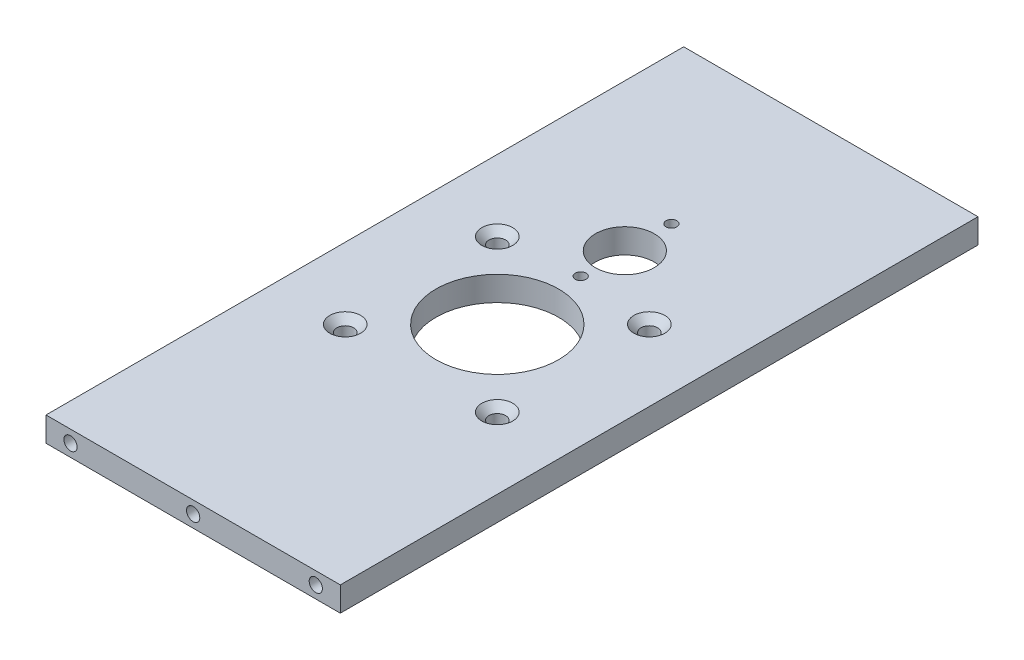
SolidWorks part; units mm, degrees
ref_plane "前基準面" through (0, 0, 0) normal (0, 0, 1) x (1, 0, 0)
ref_plane "上基準面" through (0, 0, 0) normal (0, 1, 0) x (1, 0, 0)
ref_plane "右基準面" through (0, 0, 0) normal (1, 0, 0) x (0, 0, -1)
sketch "草圖1" plane through (0, 0, 0) normal (0, 1, 0) x (1, 0, 0)
  line L1 (-30, -65) -> (30, -65)
  line L2 (-30, -65) -> (-30, 65)
  line L3 (-30, 65) -> (30, 65)
  line L4 (30, -65) -> (30, 65)
  line L5 (-30, -65) -> (30, 65) construction
  line L6 (-30, 65) -> (30, -65) construction
  point P0 (0, 0)
  dimension "D1" = 60
  dimension "D2" = 130
extrude "填料-伸長1" add sketch "草圖1" along normal blind 5
hole_wizard "M3 錐坑平頭螺釘的錐孔1" positions "草圖4" profile "草圖5" countersink size "M3" standard "ISO"
sketch "草圖4" plane through (0, 5, 0) normal (0, 1, 0) x (1, 0, 0)
  line L0 (-15.5, 12.5) -> (15.5, 12.5) construction
  line L4 (30, 65) -> (-30, 65) construction
  line L6 (15.5, 12.5) -> (-15.5, -18.5) construction
  line L8 (15.5, -18.5) -> (-15.5, 12.5) construction
  line L10 (0, -3) -> (0, 65) construction
  point P0 (-15.5, 12.5)
  point P2 (-15.5, -18.5)
  point P4 (15.5, 12.5)
  point P6 (15.5, -18.5)
  dimension "D1" = 31
  dimension "D2" = 31
  dimension "D3" = 68
sketch "草圖5" plane through (-15.5, 5, -12.5) normal (1, 0, 0) x (0, 0, 1)
  line L0 (0, 0) -> (0, 8.5215)
  line L1 (0, 8.5215) -> (1.7, 7.5)
  line L2 (1.7, 7.5) -> (1.7, 1.45)
  line L3 (1.7, 1.45) -> (3.15, 0)
  line L5 (3.15, 0) -> (0, 0)
  line L6 (-1.7, 1.45) -> (-3.15, 0) construction
  line L10 (0, 8.5215) -> (-1.7, 7.5) construction
  line L11 (0, -6.35) -> (0, 107.95) construction
  dimension "鑽孔直徑" = 3.4
  dimension "鑽孔深度" = 7.5
  dimension "近端錐孔直徑" = 6.3
  dimension "近端錐孔角度" = 90
  dimension "導頭角度" = 118
sketch "草圖6" plane through (0, 5, 0) normal (0, 1, 0) x (1, 0, 0)
  line L0 (15.5, -18.5) -> (-15.5, 12.5) construction
  line L1 (15.5, 12.5) -> (-15.5, -18.5) construction
  circle A0 centre (0, -3) radius 12.5
  dimension "D1" = 25
extrude "除料-伸長1" cut sketch "草圖6" against normal through all
hole_wizard "Ø1.0mm 定位孔2" positions "草圖7" profile "草圖8" hole size "Ø1.0" standard "ISO"
sketch "草圖7" plane through (0, 0, -65) normal (0, 0, -1) x (-1, 0, 0)
  line L0 (-25, 2.5) -> (-30, 2.5) construction
  line L1 (-30, 5) -> (-30, 0) construction
  point P0 (-25, 2.5)
  point P2 (0, 2.5)
  point P4 (25, 2.5)
  dimension "D1" = 25
  dimension "D2" = 25
sketch "草圖8" plane through (25, 2.5, -65) normal (1, 0, 0) x (0, 1, 0)
  line L0 (0, 0) -> (0, 8.3112)
  line L1 (0, 8.3112) -> (1.35, 7.5)
  line L2 (1.35, 7.5) -> (1.35, 0)
  line L5 (1.35, 0) -> (0, 0)
  line L10 (0, 8.3112) -> (-1.35, 7.5) construction
  line L11 (0, -6.35) -> (0, 107.95) construction
  dimension "鑽孔直徑" = 2.7
  dimension "鑽孔深度" = 7.5
  dimension "導頭角度" = 118
mirror "鏡射1" about plane through (0, 0, 0) normal (0, 0, 1) of "Ø1.0mm 定位孔2"
hole_wizard "Ø1.0mm 定位孔1" positions "草圖11" profile "草圖12" hole size "Ø1.0" standard "ISO" end condition through all
sketch "草圖11" plane through (0, 5, 0) normal (0, 1, 0) x (1, 0, 0)
  line L0 (30, 18) -> (-30, 18) construction
  line L1 (30, -65) -> (30, 65) construction
  line L2 (-30, 65) -> (-30, -65) construction
  line L4 (30, 28) -> (-30, 28) construction
  line L6 (30, 23) -> (-30, 23) construction
  circle A0 centre (0, -3) radius 12.5 construction
  point P0 (0, 32.5)
  point P2 (0, 14)
  dimension "D1" = 21
  dimension "D2" = 10
  dimension "D3" = 5
  dimension "D4" = 9
  dimension "D5" = 18.5
sketch "草圖12" plane through (0, 5, -32.5) normal (1, 0, 0) x (0, 0, 1)
  line L0 (0, 0) -> (0, 5)
  line L1 (0, 5) -> (1.1, 5)
  line L2 (1.1, 5) -> (1.1, 0)
  line L5 (1.1, 0) -> (0, 0)
  line L11 (0, -6.35) -> (0, 107.95) construction
  dimension "貫穿孔直徑" = 2.2
  dimension "貫穿孔深度" = 5
sketch "草圖13" plane through (0, 5, 0) normal (0, 1, 0) x (1, 0, 0)
  line L0 (0, 14) -> (0, 32.5) construction
  circle A0 centre (0, 23) radius 6
  dimension "D1" = 12
  dimension "D2" = 9.5
extrude "除料-伸長2" cut sketch "草圖13" against normal through all
